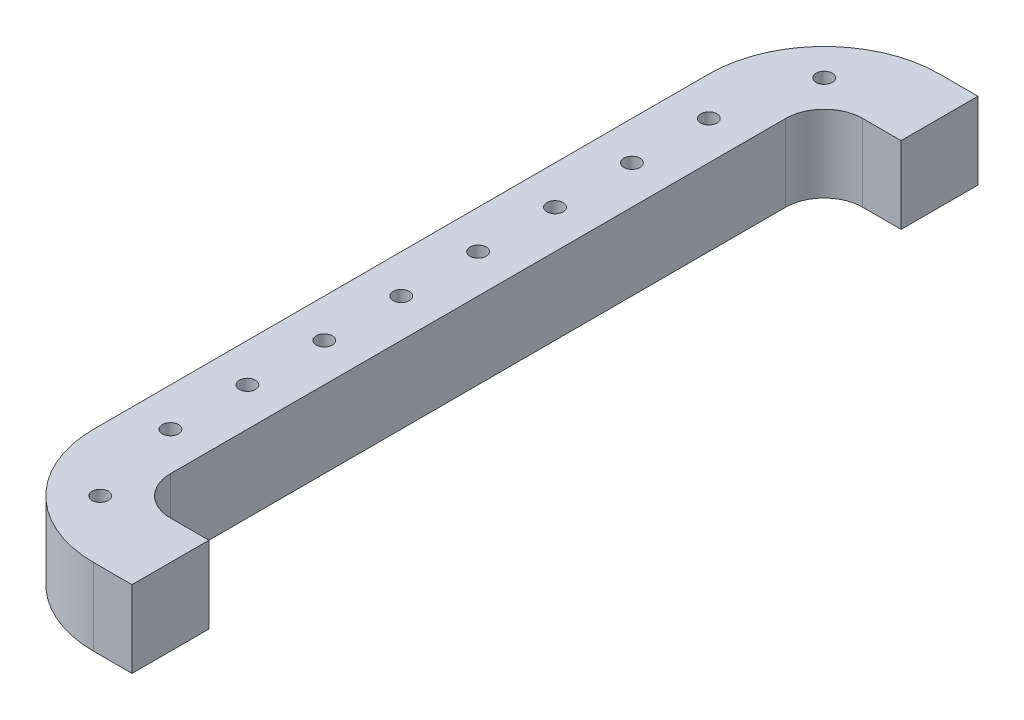
SolidWorks part; units mm, degrees
material "Custom Plastic"
ref_plane "Front Plane" through (0, 0, 0) normal (0, 0, 1) x (1, 0, 0)
ref_plane "Top Plane" through (0, 0, 0) normal (0, 1, 0) x (1, 0, 0)
ref_plane "Right Plane" through (0, 0, 0) normal (1, 0, 0) x (0, 0, -1)
sketch "Sketch1" plane through (0, 0, 0) normal (0, 1, 0) x (1, 0, 0)
  line L0 (0, 0) -> (0, 10) construction
  line L1 (20, 30) -> (30, 30) construction
  line L2 (10, 0) -> (10, 10)
  line L3 (20, 20) -> (30, 20)
  line L4 (-10, 0) -> (-10, 10)
  line L5 (20, 40) -> (30, 40)
  line L6 (10, 0) -> (-10, 0)
  line L7 (30, 20) -> (30, 40)
  arc A0 (0, 10) -> (20, 30) centre (20, 10) cw construction
  arc A1 (10, 10) -> (20, 20) centre (20, 10) cw
  arc A2 (-10, 10) -> (20, 40) centre (20, 10) cw
  point P6 (0, 30)
  dimension "D2" = 20
  dimension "D1" = 30
  dimension "D3" = 10
  dimension "D4" = 10
extrude "Boss-Extrude1" add sketch "Sketch1" along normal mid plane 20
sketch "Sketch3" plane through (0, 10, 0) normal (0, 1, 0) x (1, 0, 0)
  line L0 (-10, 10) -> (-10, 0) construction
  line L1 (10, 0) -> (-10, 0)
  line L2 (10, 0) -> (10, -70)
  line L3 (10, -70) -> (-10, -70)
  line L4 (-10, 0) -> (-10, -70)
  line L5 (30, 40) -> (20, 40) construction
  dimension "D1" = 110
extrude "Boss-Extrude2" add sketch "Sketch3" against normal up to surface (20 mm away) up to face at (11.4645, -10, -18.5355)
sketch "Sketch2" plane through (0, 10, 0) normal (0, 1, 0) x (1, 0, 0)
  line L0 (12.9289, 17.0711) -> (-1.2132, 31.2132) construction
  line L1 (0, 0) -> (0, 30) construction
  line L3 (0, 0) -> (0, -70) construction
  line L4 (-10, -70) -> (10, -70) construction
  arc A0 (20, 20) -> (10, 10) centre (20, 10) ccw construction
  arc A1 (20, 40) -> (-10, 10) centre (20, 10) ccw construction
  circle A2 centre (5.8579, 24.1421) radius 2.1
  circle A3 centre (0, -40) radius 2.1
  circle A5 centre (70, 30) radius 2.1
  circle A6 centre (0, -60) radius 2.1
  circle A7 centre (0, -20) radius 2.1
  circle A8 centre (0, 0) radius 2.1
  dimension "D1" = 4.2
  dimension "D2" = 10
  dimension "D3" = 20
  dimension "D4" = 4.2
  dimension "D6" = 20
  dimension "D5" = 3
extrude "Cut-Extrude1" cut sketch "Sketch2" against normal through all
mirror "Mirror1" about plane through (10, -82.8011, 70) normal (0, 0, 1) of bodies 102
